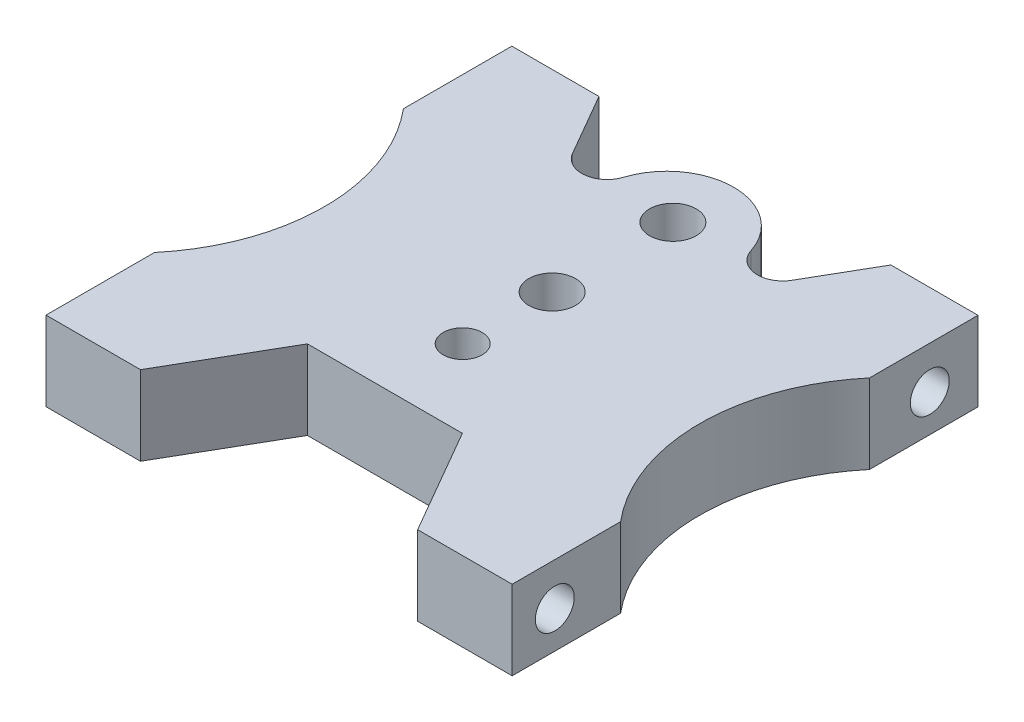
SolidWorks part; units mm, degrees
ref_plane "Piano frontale" through (0, 0, 0) normal (0, 0, 1) x (1, 0, 0)
ref_plane "Piano superiore" through (0, 0, 0) normal (0, 1, 0) x (1, 0, 0)
ref_plane "Piano destro" through (0, 0, 0) normal (1, 0, 0) x (0, 0, -1)
sketch "Schizzo1" plane through (0, 0, 0) normal (0, 1, 0) x (1, 0, 0)
  line L0 (0, -64.3941) -> (0, 53.0898) construction
  line L1 (-62.0512, 0) -> (79.4386, 0) construction
  line L3 (-14.98, 14.97) -> (14.98, 14.97)
  line L4 (-14.98, 14.97) -> (-14.98, -14.97)
  line L5 (-14.98, -14.97) -> (14.98, -14.97)
  line L6 (14.98, 14.97) -> (14.98, -14.97)
  dimension "D1" = 29.94
  dimension "D2" = 29.96
extrude "Estrusione-Estrusione1" add sketch "Schizzo1" against normal blind 5.1
sketch "Schizzo2" plane through (0, 0, 0) normal (0, 1, 0) x (1, 0, 0)
  line L0 (-8.906, -14.97) -> (-4.98, -8.17)
  line L1 (-14.98, -14.97) -> (14.98, -14.97) construction
  line L2 (-4.98, -8.17) -> (4.98, -8.17)
  line L3 (0, 0) -> (-31.8243, 0) construction
  line L4 (0, 0) -> (0, -21.317) construction
  line L5 (-8.906, -14.97) -> (-14.98, -14.97)
  line L6 (-14.98, -14.97) -> (-14.98, -8)
  line L7 (-14.98, 14.97) -> (-14.98, -14.97) construction
  line L8 (-14.98, 8) -> (-14.98, 14.97)
  line L9 (-14.98, 14.97) -> (-9.38, 14.97)
  line L10 (14.98, 14.97) -> (-14.98, 14.97) construction
  line L11 (-9.38, 14.97) -> (-7.0566, 10.9457)
  line L12 (0, 0) -> (0, 20.4645) construction
  line L13 (9.38, 14.97) -> (7.0566, 10.9457)
  line L14 (14.98, 14.97) -> (9.38, 14.97)
  line L15 (14.98, 8) -> (14.98, 14.97)
  line L16 (14.98, -14.97) -> (14.98, -8)
  line L17 (8.906, -14.97) -> (14.98, -14.97)
  line L18 (8.906, -14.97) -> (4.98, -8.17)
  line L19 (14.98, -14.97) -> (14.98, 14.97) construction
  line L20 (14.98, 14.97) -> (-14.98, 14.97)
  line L21 (-14.98, 14.97) -> (-14.98, -14.97)
  line L22 (-14.98, -14.97) -> (14.98, -14.97)
  line L23 (14.98, -14.97) -> (14.98, 14.97)
  arc A0 (-14.98, -8) -> (-14.98, 8) centre (-24.5002, 0) ccw
  arc A1 (-7.0566, 10.9457) -> (-4.09, 11.2643) centre (-5.6438, 11.7613) ccw
  arc A2 (-4.09, 11.2643) -> (4.09, 11.2643) centre (0, 9.9558) cw
  arc A3 (7.0566, 10.9457) -> (4.09, 11.2643) centre (5.6438, 11.7613) cw
  arc A4 (14.98, -8) -> (14.98, 8) centre (24.5002, 0) cw
  point P6 (-12.065, 0)
  point P37 (0, -8.17)
  point P38 (12.065, 0)
  point P39 (0, 14.25)
  point P40 (-5.6438, 10.13)
  line M19 (-14.98, 14.97) -> (-14.98, -14.97)
  line M20 (-14.98, -14.97) -> (14.98, -14.97)
  line M21 (14.98, -14.97) -> (14.98, 14.97)
  line M22 (14.98, 14.97) -> (-14.98, 14.97)
  dimension "D3" = 24.13
  dimension "D5" = 22.42
  dimension "D10" = 8.18
  dimension "D1" = 60
  dimension "D2" = 60
  dimension "D4" = 16
  dimension "D6" = 18.3
  dimension "D7" = 6.8
  dimension "D8" = 10
  dimension "D9" = 5.6
extrude "Taglio-Estrusione1" cut sketch "Schizzo2" against normal blind 5.1 contours L18 L2 L0 M20 | A4 M21 | A3 L13 L11 A1 A2 M22 | A0 M19
sketch "Schizzo3" plane through (0, 0, 0) normal (0, 1, 0) x (1, 0, 0)
  line L0 (0, 15.9233) -> (0, -15.8796) construction
  circle A0 centre (0, 10.34) radius 1.5
  circle A1 centre (0, 2.58) radius 1.5
  arc A3 (4.09, 11.2643) -> (-4.09, 11.2643) centre (0, 9.9558) ccw construction
  point P9 (0, 11.84)
  point P10 (0, 4.08)
  point P12 (0, 14.25)
  dimension "D1" = 3
  dimension "D2" = 3
  dimension "D4" = 2.41
  dimension "D5" = 10.17
extrude "Taglio-Estrusione2" cut sketch "Schizzo3" against normal through all
hole_wizard "Foro filettato M3x0.5-1" positions "Schizzo5" profile "Schizzo4" tap size "M3x0.5" standard "Ansi Metric" end condition through all
sketch "Schizzo5" plane through (0, 0, 0) normal (0, 1, 0) x (1, 0, 0)
  line L0 (-4.98, -8.17) -> (4.98, -8.17) construction
  point P0 (0, -3.17)
  dimension "D1" = 5
sketch "Schizzo4" plane through (0, 0, 3.17) normal (1, 0, 0) x (0, 0, 1)
  line L0 (0, 0) -> (0, 5.1)
  line L1 (0, 5.1) -> (1.25, 5.1)
  line L2 (1.25, 5.1) -> (1.25, 0)
  line L5 (1.25, 0) -> (0, 0)
  line L11 (0, -6.35) -> (0, 107.95) construction
  dimension "Thread Major Dia." = 2.5
  dimension "Thru Tap Drill Depth" = 5.1
hole_wizard "Foro filettato M3x0.5-2" positions "Schizzo6" profile "Schizzo7" tap size "M3x0.5" standard "Ansi Metric"
sketch "Schizzo6" plane through (16.95, 0, 0) normal (1, 0, 0) x (0, 0, -1)
  point P0 (-12.23, -2.72)
  point P3 (11.87, -2.72)
sketch "Schizzo7" plane through (16.95, -2.72, 12.23) normal (0, 1, 0) x (0, 0, -1)
  line L0 (0, 0) -> (0, 10.7511)
  line L1 (0, 10.7511) -> (1.25, 10)
  line L2 (1.25, 10) -> (1.25, 0)
  line L3 (1.25, 0) -> (0, 0)
  line L4 (0, 10.7511) -> (-1.25, 10) construction
  line L5 (0, -6.35) -> (0, 107.95) construction
  dimension "Tap Drill Dia." = 2.5
  dimension "Tap Drill Depth" = 10
  dimension "Drill Angle" = 118
cosmetic thread "Filettatura del foro1" parameters "D1"=10, "D2"=3
cosmetic thread "Filettatura del foro2" parameters "D1"=10, "D2"=3
